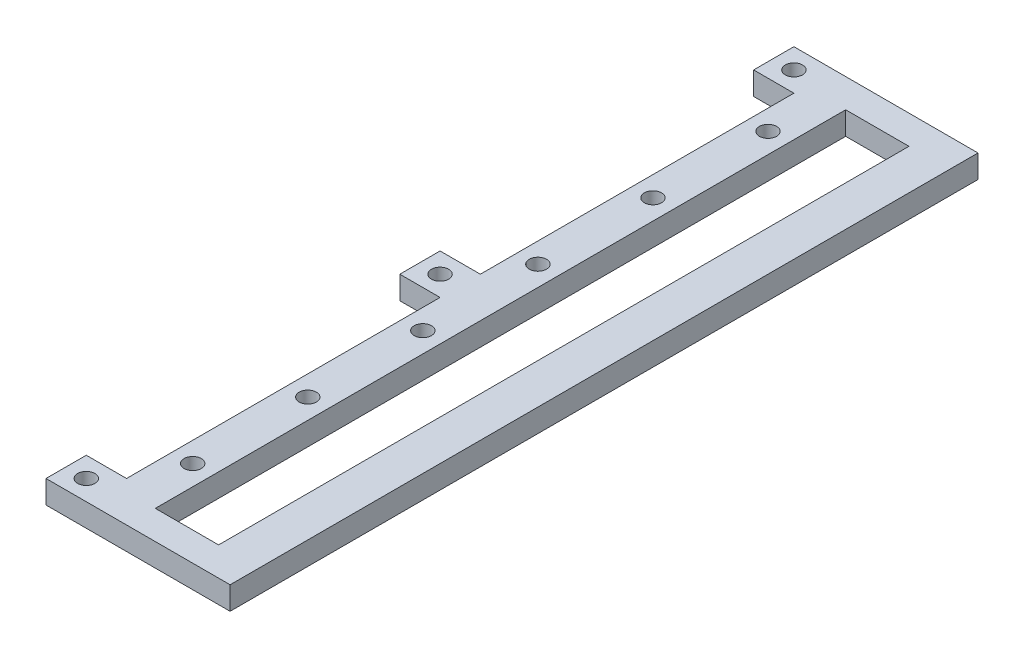
SolidWorks part; units mm, degrees
ref_plane "Front Plane" through (0, 0, 0) normal (0, 0, 1) x (1, 0, 0)
ref_plane "Top Plane" through (0, 0, 0) normal (0, 1, 0) x (1, 0, 0)
ref_plane "Right Plane" through (0, 0, 0) normal (1, 0, 0) x (0, 0, -1)
sketch "Sketch1" plane through (0, 0, 0) normal (0, 1, 0) x (1, 0, 0)
  line L0 (-12.5, 0) -> (12.5, 0) construction
  line L1 (-12.5, 65) -> (12.5, 65)
  line L3 (-12.5, -65) -> (12.5, -65)
  line L4 (12.5, 65) -> (12.5, -65)
  line L5 (-12.5, 65) -> (12.5, -65) construction
  line L6 (-12.5, -65) -> (12.5, 65) construction
  line L10 (-5.5, 60) -> (5.5, 60)
  line L11 (-5.5, 60) -> (-5.5, -60)
  line L12 (-5.5, -60) -> (5.5, -60)
  line L13 (5.5, 60) -> (5.5, -60)
  line L14 (-12.5, 65) -> (-19.5, 65)
  line L15 (-19.5, 65) -> (-19.5, 58)
  line L16 (-19.5, 58) -> (-12.5, 58)
  line L17 (-12.5, 3.5) -> (-19.5, 3.5)
  line L18 (-19.5, 3.5) -> (-19.5, -3.5)
  line L19 (-19.5, -3.5) -> (-12.5, -3.5)
  line L20 (-19.5, 0) -> (-12.5, 0) construction
  line L21 (-19.5, 61.5) -> (-12.5, 61.5) construction
  line L22 (-19.5, -58) -> (-12.5, -58)
  line L23 (-19.5, -65) -> (-19.5, -58)
  line L24 (-12.5, -65) -> (-19.5, -65)
  line L25 (-12.5, 58) -> (-12.5, 3.5)
  line L26 (-12.5, -3.5) -> (-12.5, -58)
  circle A4 centre (-9, 50) radius 1.5
  circle A7 centre (-16, 61.5) radius 1.5
  circle A8 centre (-16, 0) radius 1.5
  circle A9 centre (-16, -61.5) radius 1.5
  circle A10 centre (-9, -50) radius 1.5
  circle A11 centre (-9, 30) radius 1.5
  circle A12 centre (-9, 10) radius 1.5
  circle A13 centre (-9, -10) radius 1.5
  circle A14 centre (-9, -30) radius 1.5
  point P0 (0, 0)
  dimension "D14" = 3
  dimension "D1" = 130
  dimension "D2" = 25
  dimension "D3" = 5
  dimension "D4" = 11
  dimension "D5" = 5
  dimension "D6" = 5
  dimension "D10" = 7
  dimension "D11" = 7
  dimension "D12" = 7
  dimension "D13" = 7
  dimension "16" = 15
extrude "Boss-Extrude1" add sketch "Sketch1" along normal blind 4
